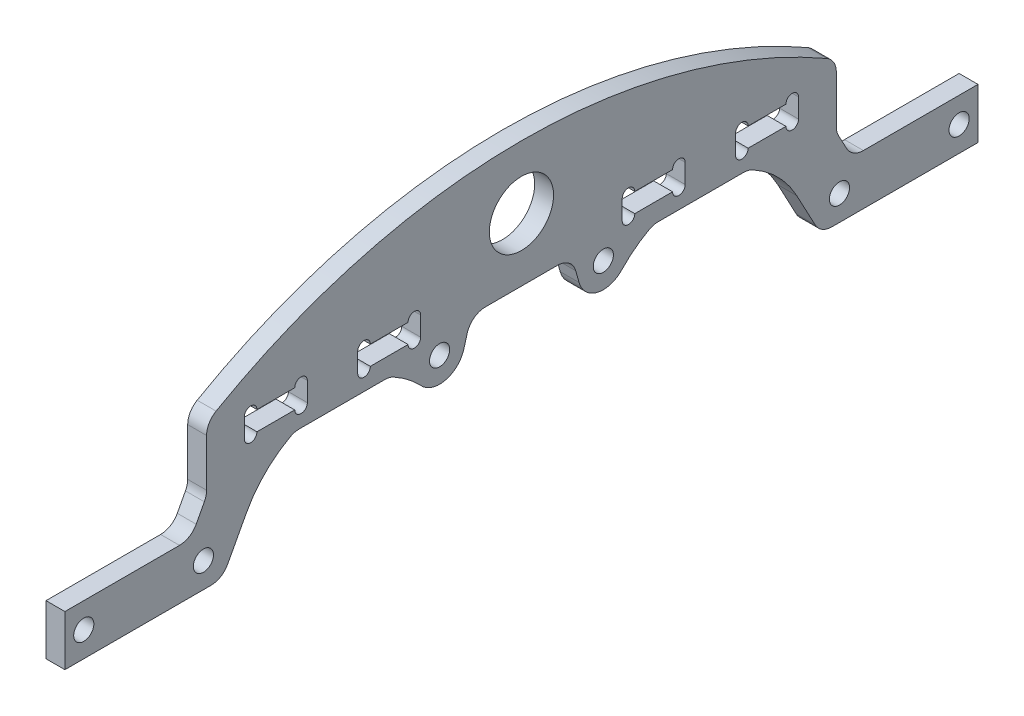
SolidWorks part; units mm, degrees
material "碳板"
ref_plane "前视基准面" through (0, 0, 0) normal (0, 0, 1) x (1, 0, 0)
ref_plane "上视基准面" through (0, 0, 0) normal (0, 1, 0) x (1, 0, 0)
ref_plane "右视基准面" through (0, 0, 0) normal (1, 0, 0) x (0, 0, -1)
sketch "草图2" plane through (0, 0, 0) normal (1, 0, 0) x (0, 0, -1)
  line L0 (0, 92.2326) -> (0, -91.3953) construction
  line L1 (-120.8372, 0) -> (103.814, 0) construction
  line L2 (-60, 92.2326) -> (-60, -88.6047) construction
  line L3 (-33.9363, 30.078) -> (-47.0958, 5.4379) construction
  line L4 (-36, 7.5) -> (-21, 7.5) construction
  line L5 (-36, 7.5) -> (-36, -7.5) construction
  line L6 (-36, -7.5) -> (-21, -7.5) construction
  line L7 (-21, 7.5) -> (-21, -7.5) construction
  line L8 (-36, 7.5) -> (-21, -7.5) construction
  line L9 (-36, -7.5) -> (-21, 7.5) construction
  line L10 (-47.5, -4) -> (-72.5, -4)
  line L11 (-72.5, 4) -> (-72.5, -4)
  line L12 (-47.5, -4) -> (-43.71, 3.0964)
  line L13 (-21, 7.5) -> (-21, 10.5) construction
  line L14 (47.5, -4) -> (43.71, 3.0964)
  line L16 (47.5, -4) -> (72.5, -4)
  line L17 (72.5, 4) -> (72.5, -4)
  line L18 (-9.1497, 8.4161) -> (-8, 12.5)
  line L19 (-8, 12.5) -> (8, 12.5)
  line L20 (9.1497, 8.4161) -> (8, 12.5)
  line L21 (-72.5, 4) -> (-52.5, 4)
  line L22 (-52.5, 4) -> (-50, 8.681)
  line L23 (52.5, 4) -> (50, 8.681)
  line L24 (72.5, 4) -> (52.5, 4)
  line L28 (-21, 10.5) -> (-36, 10.5)
  line L29 (-50, 8.681) -> (-50, 18.681)
  line L30 (50, 8.681) -> (50, 18.681)
  line L31 (21, 10.5) -> (36, 10.5)
  circle A0 centre (-69.5, 0) radius 1.6
  circle A1 centre (-50.5, 0) radius 1.6
  circle A2 centre (50.5, 0) radius 1.6
  circle A3 centre (69.5, 0) radius 1.6
  circle A4 centre (0, 22.5) radius 5.1
  circle A5 centre (-13, 9.5) radius 1.6
  circle A6 centre (13, 9.5) radius 1.6
  circle A7 centre (-13, 9.5) radius 4
  arc A8 (-43.71, 3.0964) -> (-36, 10.5) centre (-28.5, -5.0268) cw
  circle A9 centre (0, 22.5) radius 10
  circle A10 centre (13, 9.5) radius 4
  arc A11 (43.71, 3.0964) -> (36, 10.5) centre (28.5, -5.0268) ccw
  arc A12 (-50, 18.681) -> (50, 18.681) centre (0, -64.8649) cw
  arc A37 (-21, 10.5) -> (-15.9186, 6.7647) centre (-28.5, -5.0268) cw
  arc A38 (21, 10.5) -> (15.9186, 6.7647) centre (28.5, -5.0268) ccw
  point P15 (-28.5, 0)
  point P32 (-60, -4)
  point P40 (-72.5, 0)
  point P50 (-28.5, 7.5)
  point P52 (0, 12.5)
  dimension "D2" = 3.2
  dimension "D6" = 10.2
  dimension "D8" = 3.2
  dimension "D11" = 8
  dimension "D14" = 3
  dimension "D15" = 20
  dimension "D16" = 16
  dimension "D17" = 20
  dimension "D18" = 2.5
  dimension "D1" = 60
  dimension "D3" = 19
  dimension "D4" = 15
  dimension "D5" = 28.5
  dimension "D7" = 22.5
  dimension "D9" = 26
  dimension "D10" = 9.5
  dimension "D12" = 4
  dimension "D13" = 25
  dimension "D19" = 10
extrude "凸台-拉伸1" add sketch "草图2" along normal blind 3
sketch "草图3" plane through (3, 0, 0) normal (1, 0, 0) x (0, 0, -1)
  line L0 (0, 43.3546) -> (0, -12.7822) construction
  line L1 (-57.5196, 15) -> (59.5594, 15) construction
  line L2 (-26, 16.525) -> (-26, 13.475)
  line L3 (-44, 16.525) -> (-34, 16.525)
  line L4 (-44, 16.525) -> (-44, 13.475)
  line L5 (-44, 13.475) -> (-34, 13.475)
  line L6 (-34, 16.525) -> (-34, 13.475)
  line L7 (-44, 16.525) -> (-34, 13.475) construction
  line L8 (-44, 13.475) -> (-34, 16.525) construction
  line L9 (-26, 16.525) -> (-16, 16.525)
  line L10 (-16, 16.525) -> (-16, 13.475)
  line L11 (-26, 13.475) -> (-16, 13.475)
  line L12 (-44, 16.525) -> (-26, 16.525) construction
  line L13 (44, 16.525) -> (26, 16.525) construction
  line L14 (44, 13.475) -> (34, 16.525) construction
  line L15 (44, 16.525) -> (34, 13.475) construction
  line L16 (26, 13.475) -> (16, 13.475)
  line L17 (16, 16.525) -> (16, 13.475)
  line L18 (26, 16.525) -> (16, 16.525)
  line L19 (34, 16.525) -> (34, 13.475)
  line L20 (44, 13.475) -> (34, 13.475)
  line L21 (44, 16.525) -> (44, 13.475)
  line L22 (44, 16.525) -> (34, 16.525)
  line L23 (26, 16.525) -> (26, 13.475)
  circle A0 centre (0, 22.5) radius 5.1 construction
  circle A1 centre (-43, 16.525) radius 1
  circle A2 centre (-43, 13.475) radius 1
  circle A3 centre (-35, 16.525) radius 1
  circle A4 centre (-35, 13.475) radius 1
  circle A5 centre (-25, 16.525) radius 1
  circle A6 centre (-17, 16.525) radius 1
  circle A7 centre (-17, 13.475) radius 1
  circle A8 centre (-25, 13.475) radius 1
  circle A9 centre (25, 13.475) radius 1
  circle A10 centre (17, 13.475) radius 1
  circle A11 centre (17, 16.525) radius 1
  circle A12 centre (25, 16.525) radius 1
  circle A13 centre (35, 13.475) radius 1
  circle A14 centre (35, 16.525) radius 1
  circle A15 centre (43, 13.475) radius 1
  circle A16 centre (43, 16.525) radius 1
  point P7 (-39, 15)
  point P58 (39, 15)
  dimension "D2" = 2
  dimension "D1" = 7.5
  dimension "D3" = 3.05
  dimension "D4" = 10
  dimension "D6" = 18
  dimension "D7" = 32
  dimension "D5" = 2
extrude "切除-拉伸1" cut sketch "草图3" against normal through all contours L3 L6 L5 L4 | A1 | A2 | A3 | A4 | L9 L10 L11 L2 | A5 | A8 | A6 | A7 | L16 L17 L18 L23 | A11 | A10 | A12 | A9 | L22 L19 L20 L21 | A14 | A13 | A16 | A15
fillet "圆角1" radius 3 14 edges at (1.5, -4, -47.5) (1.5, -4, 47.5) (1.5, 10.5, -36) (1.5, 10.5, -21) (1.5, 12.5, -8) (1.5, 12.5, 8) (1.5, 10.5, 21) (1.5, 10.5, 36) (1.5, 4, -52.5) (1.5, 8.681, -50) (1.5, 18.681, -50) (1.5, 18.681, 50) (1.5, 8.681, 50) (1.5, 4, 52.5)
